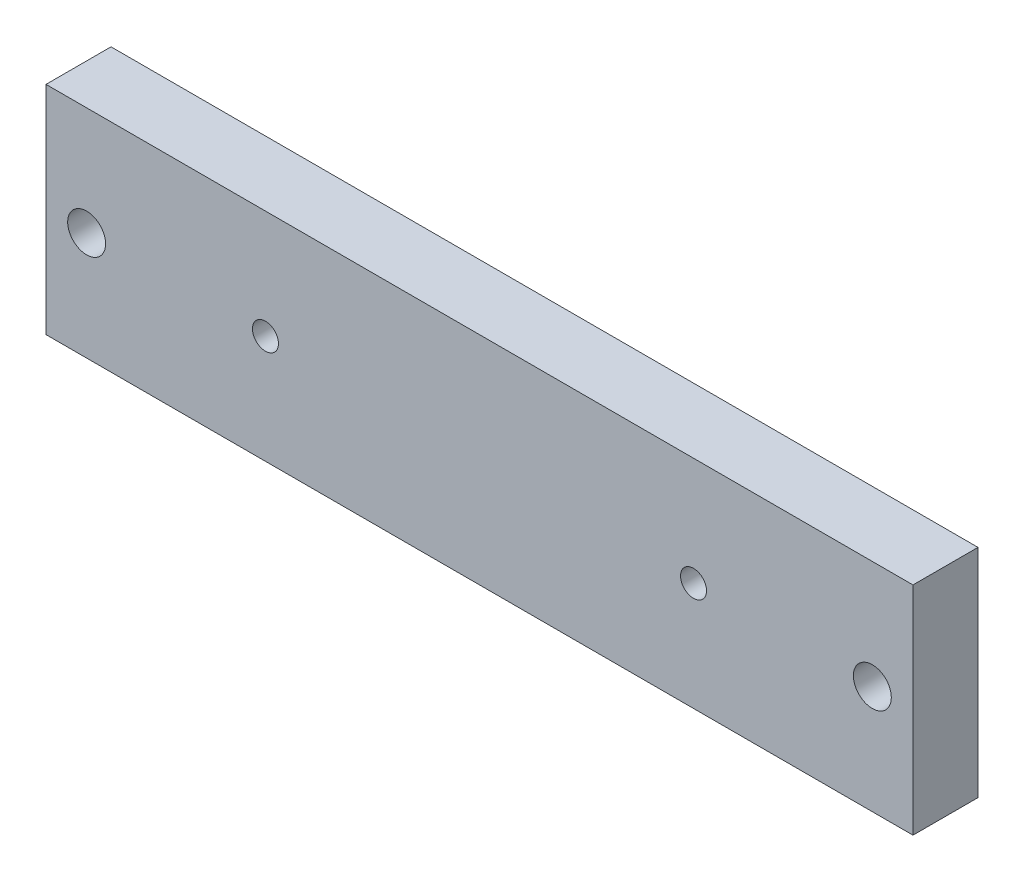
SolidWorks part; units mm, degrees
material "6061-T6 (SS)"
ref_plane "Front Plane" through (0, 0, 0) normal (0, 0, 1) x (1, 0, 0)
ref_plane "Top Plane" through (0, 0, 0) normal (0, 1, 0) x (1, 0, 0)
ref_plane "Right Plane" through (0, 0, 0) normal (1, 0, 0) x (0, 0, -1)
sketch "Sketch1" plane through (0, 0, 0) normal (0, 0, 1) x (1, 0, 0)
  line L0 (0, 0) -> (-39.5, 0) construction
  line L1 (-80, 20) -> (80, 20)
  line L2 (-80, 20) -> (-80, -20)
  line L3 (-80, -20) -> (80, -20)
  line L4 (80, 20) -> (80, -20)
  line L5 (-80, 20) -> (80, -20) construction
  line L6 (-80, -20) -> (80, 20) construction
  line L7 (-39.5, 0) -> (-72.5, 0) construction
  line L8 (0, 0) -> (39.5, 0) construction
  line L9 (39.5, 0) -> (72.5, 0) construction
  line L11 (60, 20) -> (-60, 20) construction
  line L12 (60, 20) -> (60, -20) construction
  line L13 (60, -20) -> (-60, -20) construction
  line L14 (-60, 20) -> (-60, -20) construction
  line L15 (60, 20) -> (-60, -20) construction
  line L16 (60, -20) -> (-60, 20) construction
  point P0 (0, 0)
  dimension "D1" = 160
  dimension "D2" = 40
  dimension "D3" = 79
  dimension "D4" = 145
  dimension "D5" = 120
extrude "Boss-Extrude1" add sketch "Sketch1" along normal blind 12
hole_wizard "M6 Clearance Hole1" positions "Sketch3" profile "Sketch2" hole size "M6" standard "ANSI Metric" end condition up to next
sketch "Sketch3" plane through (0, 0, 12) normal (0, 0, 1) x (1, 0, 0)
  point P0 (-72.5, 0)
  point P3 (72.5, 0)
sketch "Sketch2" plane through (-72.5, 0, 12) normal (1, 0, 0) x (0, -1, 0)
  line L0 (0, 0) -> (0, 12)
  line L1 (0, 12) -> (3.5, 12)
  line L2 (3.5, 12) -> (3.5, 0)
  line L5 (3.5, 0) -> (0, 0)
  line L11 (0, -6.35) -> (0, 107.95) construction
  dimension "Thru Hole Dia." = 7
  dimension "Thru Hole Depth" = 12
hole_wizard "CBORE for M4 SHCS1" positions "Sketch5" profile "Sketch4" counterbore size "M4" standard "ANSI Metric" end condition through all
sketch "Sketch5" plane through (0, 0, 0) normal (0, 0, -1) x (-1, 0, 0)
  point P0 (-39.5, 0)
  point P3 (39.5, 0)
sketch "Sketch4" plane through (39.5, 0, 0) normal (1, 0, 0) x (0, 1, 0)
  line L0 (0, 0) -> (0, 12)
  line L1 (0, 12) -> (2.4, 12)
  line L3 (2.4, 12) -> (2.4, 4)
  line L4 (2.4, 4) -> (4, 4)
  line L5 (4, 4) -> (4, 0)
  line L7 (4, 0) -> (0, 0)
  line L11 (0, -6.35) -> (0, 107.95) construction
  dimension "Thru Hole Dia." = 4.8
  dimension "Thru Hole Depth" = 12
  dimension "C'Bore Dia." = 8
  dimension "C'Bore Depth" = 4
